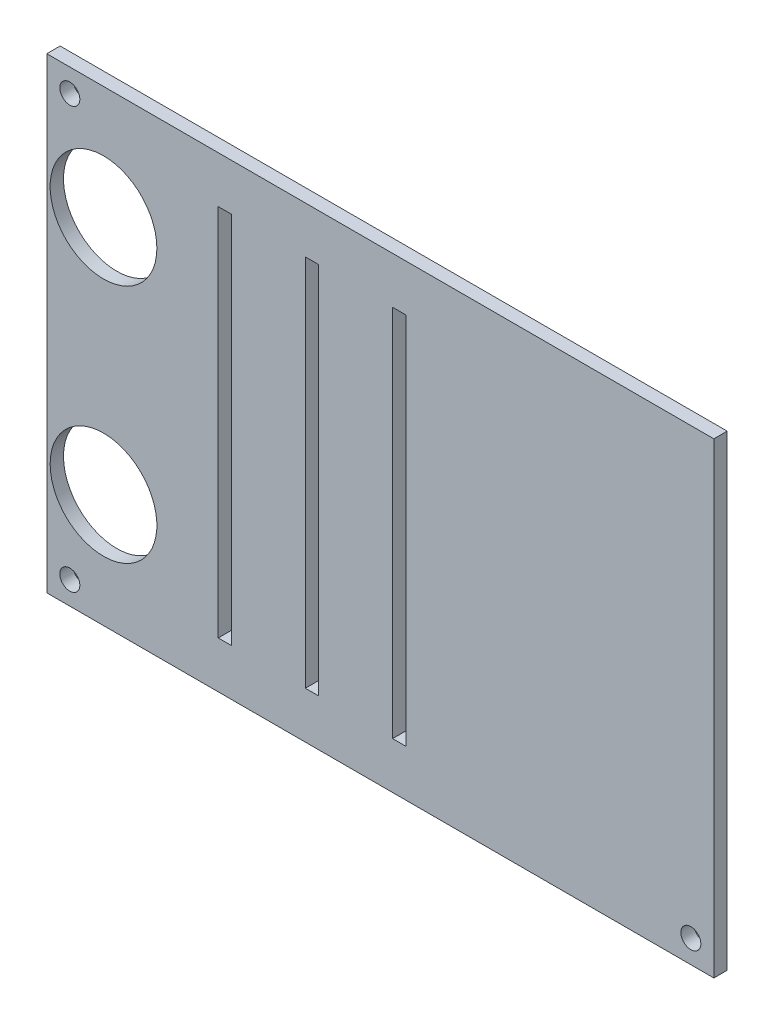
SolidWorks part; units mm, degrees
ref_plane "正面" through (0, 0, 0) normal (0, 0, 1) x (1, 0, 0)
ref_plane "平面" through (0, 0, 0) normal (0, 1, 0) x (1, 0, 0)
ref_plane "右側面" through (0, 0, 0) normal (1, 0, 0) x (0, 0, -1)
sketch "ｽｹｯﾁ1" plane through (0, 0, 0) normal (0, 0, 1) x (1, 0, 0)
  line L0 (50, 0) -> (50, -70) construction
  line L1 (0, 0) -> (100, 0)
  line L2 (0, 0) -> (0, -70)
  line L3 (0, -70) -> (100, -70)
  line L4 (100, 0) -> (100, -70)
  line L5 (100, -35) -> (0, -35) construction
  line L6 (39.76, -5) -> (39.76, -65) construction
  line L7 (51.84, -63) -> (51.84, -7)
  line L8 (36.76, -5) -> (42.76, -5) construction
  line L9 (36.76, -5) -> (36.76, -65) construction
  line L10 (36.76, -65) -> (42.76, -65) construction
  line L11 (42.76, -5) -> (42.76, -65) construction
  line L12 (38.76, -63) -> (40.76, -63)
  line L13 (38.76, -63) -> (38.76, -7)
  line L14 (38.76, -7) -> (40.76, -7)
  line L15 (40.76, -63) -> (40.76, -7)
  line L16 (38.76, -63) -> (40.76, -7) construction
  line L17 (38.76, -7) -> (40.76, -63) construction
  line L18 (51.84, -7) -> (53.84, -7)
  line L19 (53.84, -63) -> (53.84, -7)
  line L20 (51.84, -63) -> (53.84, -63)
  line L21 (25.7, -63) -> (25.7, -7)
  line L22 (27.7, -63) -> (27.7, -7)
  line L23 (25.7, -63) -> (27.7, -63)
  line L24 (25.7, -7) -> (27.7, -7)
  circle A0 centre (3.45, -3.45) radius 1.5
  circle A1 centre (3.45, -66.55) radius 1.5
  circle A2 centre (96.55, -66.55) radius 1.5
  circle A4 centre (8.5, -17) radius 8
  circle A5 centre (8.5, -53) radius 8
  point P25 (39.76, -35)
  dimension "D5" = 3
  dimension "D6" = 17
  dimension "D8" = 16
  dimension "D9" = 2
  dimension "D1" = 70
  dimension "D2" = 100
  dimension "D3" = 3.45
  dimension "D4" = 3.45
  dimension "D7" = 8.5
  dimension "D10" = 36.76
  dimension "D11" = 6
  dimension "D12" = 60
  dimension "D13" = 5
  dimension "D14" = 56
  dimension "D17" = 13.06
  dimension "D18" = 13.08
  dimension "D15" = 2
  dimension "D16" = 2
extrude "ﾎﾞｽ - 押し出し1" add sketch "ｽｹｯﾁ1" along normal blind 2
